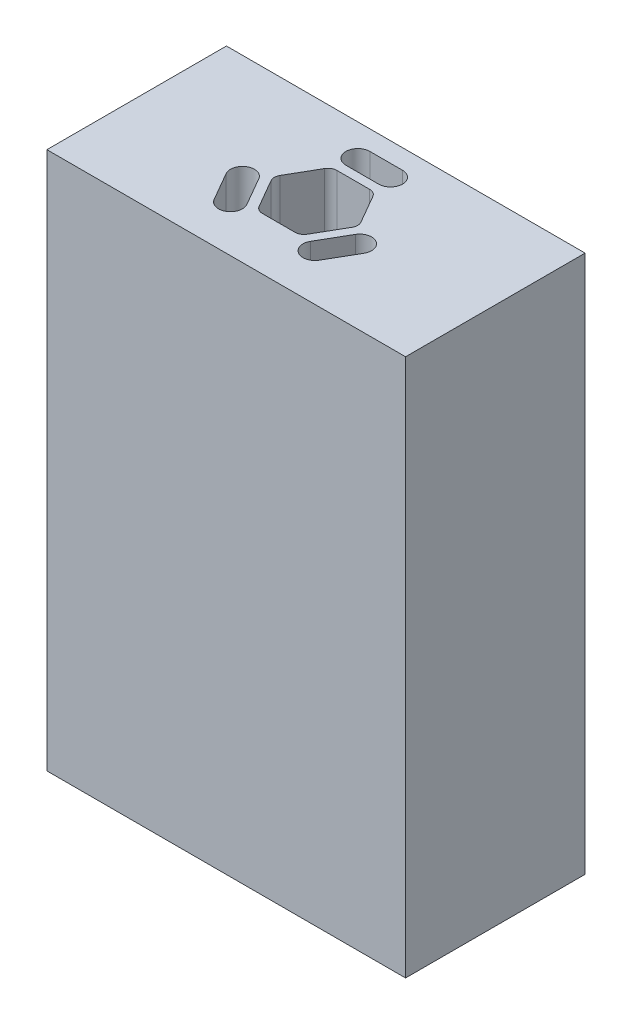
SolidWorks part; units mm, degrees
ref_plane "Front Plane" through (0, 0, 0) normal (0, 0, 1) x (1, 0, 0)
ref_plane "Top Plane" through (0, 0, 0) normal (0, 1, 0) x (1, 0, 0)
ref_plane "Right Plane" through (0, 0, 0) normal (1, 0, 0) x (0, 0, -1)
sketch "Sketch1" plane through (0, 0, 0) normal (0, 1, 0) x (1, 0, 0)
  line L0 (-0.0911, 0.2578) -> (0.0911, 0.2578)
  line L1 (-0.1344, 0.1828) -> (-0.2256, 0.025)
  line L2 (-0.2256, -0.025) -> (-0.1344, -0.1828)
  line L3 (-0.0911, -0.2078) -> (0.0911, -0.2078)
  line L4 (0.1344, -0.1828) -> (0.2256, -0.025)
  line L5 (0.2256, 0.025) -> (0.1344, 0.1828)
  line L6 (0.0911, 0.2078) -> (-0.0911, 0.2078)
  line L7 (-0.0911, 0.3914) -> (0.0911, 0.3914)
  line L8 (0, 0) -> (0.4855, 0.2803) construction
  line L9 (0.2934, -0.2746) -> (0.3846, -0.1168)
  line L10 (0.1777, -0.2078) -> (0.2689, -0.05)
  line L11 (0, 0) -> (-0.3106, 0.1793) construction
  line L12 (-0.3846, -0.1168) -> (-0.2934, -0.2746)
  line L13 (-0.2689, -0.05) -> (-0.1777, -0.2078)
  circle A0 centre (0, 0) radius 0.24 construction
  circle A1 centre (0, 0) radius 0.24 construction
  arc A2 (-0.1344, 0.1828) -> (-0.0911, 0.2078) centre (-0.0911, 0.1578) cw
  arc A3 (0.1344, 0.1828) -> (0.0911, 0.2078) centre (0.0911, 0.1578) ccw
  arc A4 (-0.2256, -0.025) -> (-0.2256, 0.025) centre (-0.1823, 0) cw
  arc A5 (-0.1344, -0.1828) -> (-0.0911, -0.2078) centre (-0.0911, -0.1578) ccw
  arc A6 (0.0911, -0.2078) -> (0.1344, -0.1828) centre (0.0911, -0.1578) ccw
  arc A7 (0.2256, -0.025) -> (0.2256, 0.025) centre (0.1823, 0) ccw
  arc A8 (-0.0911, 0.2578) -> (-0.0911, 0.3914) centre (-0.0911, 0.3246) cw
  arc A9 (0.0911, 0.2578) -> (0.0911, 0.3914) centre (0.0911, 0.3246) ccw
  arc A10 (0.2689, -0.05) -> (0.3846, -0.1168) centre (0.3267, -0.0834) cw
  arc A11 (0.1777, -0.2078) -> (0.2934, -0.2746) centre (0.2356, -0.2412) ccw
  arc A12 (-0.1777, -0.2078) -> (-0.2934, -0.2746) centre (-0.2356, -0.2412) cw
  arc A13 (-0.2689, -0.05) -> (-0.3846, -0.1168) centre (-0.3267, -0.0834) ccw
  point P12 (-0.12, 0.2078)
  dimension "D2" = 0.05
  dimension "D3" = 0.05
  dimension "D4" = 0.05
  dimension "D5" = 0.05
  dimension "D6" = 0.05
  dimension "D7" = 0.05
  dimension "D8" = 0.05
sketch "Sketch6" plane through (0, 0, 0) normal (0, -1, 0) x (1, 0, 0)
  line L1 (1, 0.5006) -> (-1, 0.5006)
  line L2 (1, 0.5006) -> (1, -0.5006)
  line L3 (1, -0.5006) -> (-1, -0.5006)
  line L4 (-1, 0.5006) -> (-1, -0.5006)
  line L5 (1, 0.5006) -> (-1, -0.5006) construction
  line L6 (1, -0.5006) -> (-1, 0.5006) construction
  point P0 (0, 0)
extrude "Boss-Extrude7" add sketch "Sketch6" along normal blind 3
sketch "Sketch5" plane through (0, 0.6, 0) normal (0, 1, 0) x (1, 0, 0)
  line L0 (-0.1344, -0.1828) -> (-0.2256, -0.025) construction
  circle A0 centre (0, 0) radius 0.2078
extrude "Cut-Extrude3" cut sketch "Sketch1" against normal blind 0.9
extrude "Cut-Extrude4" cut sketch "Sketch5" against normal blind 2.7 contours A0
